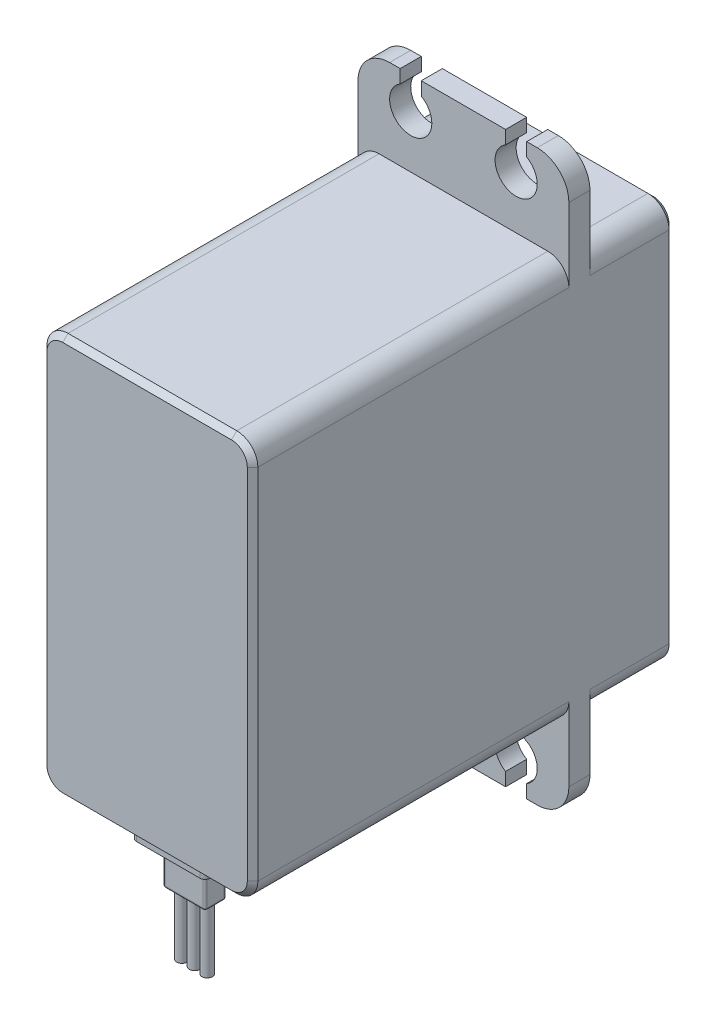
SolidWorks part; units mm, degrees
ref_plane "前视基准面" through (0, 0, 0) normal (0, 0, 1) x (1, 0, 0)
ref_plane "上视基准面" through (0, 0, 0) normal (0, 1, 0) x (1, 0, 0)
ref_plane "右视基准面" through (0, 0, 0) normal (1, 0, 0) x (0, 0, -1)
sketch "草图1" plane through (0, 0, 0) normal (0, 0, 1) x (1, 0, 0)
  line L1 (-10, -27) -> (10, -27)
  line L2 (-10, -27) -> (-10, 27)
  line L3 (-10, 27) -> (10, 27)
  line L4 (10, -27) -> (10, 27)
  line L5 (-10, -27) -> (10, 27) construction
  line L6 (-10, 27) -> (10, -27) construction
  point P0 (0, 0)
  dimension "D1" = 20
  dimension "D2" = 54
extrude "凸台-拉伸1" add sketch "草图1" along normal blind 40
sketch "草图2" plane through (0, 0, 40) normal (0, 0, 1) x (1, 0, 0)
  line L0 (10, -27) -> (10, 27) construction
  line L1 (-10, -19) -> (10, -19)
  line L2 (-10, -19) -> (-10, 19)
  line L3 (-10, 19) -> (10, 19)
  line L4 (10, -19) -> (10, 19)
  line L5 (-10, -19) -> (10, 19) construction
  line L6 (-10, 19) -> (10, -19) construction
  point P0 (0, 0)
  dimension "D1" = 38
extrude "切除-拉伸1" cut sketch "草图2" against normal blind 30 flip side to cut
sketch "草图3" plane through (0, 0, 0) normal (0, 0, -1) x (-1, 0, 0)
  line L0 (10, 27) -> (10, -27) construction
  line L1 (-10, -19) -> (10, -19)
  line L2 (-10, -19) -> (-10, 19)
  line L3 (-10, 19) -> (10, 19)
  line L4 (10, -19) -> (10, 19)
  line L5 (-10, -19) -> (10, 19) construction
  line L6 (-10, 19) -> (10, -19) construction
  point P0 (0, 0)
  dimension "D1" = 38
extrude "切除-拉伸2" cut sketch "草图3" against normal blind 8 flip side to cut
sketch "草图4" plane through (0, 0, 10) normal (0, 0, 1) x (1, 0, 0)
  line L0 (4, 25.7321) -> (4, 27)
  line L1 (10, 27) -> (-10, 27) construction
  line L2 (4, 27) -> (6, 27)
  line L3 (6, 27) -> (6, 25.7321)
  line L4 (5, 24) -> (5, 27) construction
  line L5 (10, 19) -> (10, 27) construction
  line L6 (-6, 25.7321) -> (-6, 27)
  line L7 (-4, 27) -> (-4, 25.7321)
  line L8 (-6, 27) -> (-4, 27)
  arc A0 (4, 25.7321) -> (6, 25.7321) centre (5, 24) ccw
  arc A1 (-6, 25.7321) -> (-4, 25.7321) centre (-5, 24) ccw
  dimension "D1" = 2
  dimension "D2" = 3
  dimension "D3" = 2
  dimension "D4" = 4
  dimension "D6" = 10
  dimension "D5" = 2
extrude "切除-拉伸3" cut sketch "草图4" against normal through all
mirror "镜向1" about plane through (0, 0, 0) normal (0, 1, 0) of "切除-拉伸3"
sketch "草图6" plane through (0, -19, 0) normal (0, -1, 0) x (1, 0, 0)
  line L0 (0, 0) -> (0, 40) construction
  line L1 (-10, 40) -> (10, 40) construction
  line L3 (3.5, 38) -> (-3.5, 38)
  line L4 (3.5, 38) -> (3.5, 33)
  line L5 (3.5, 33) -> (-3.5, 33)
  line L6 (-3.5, 38) -> (-3.5, 33)
  line L7 (3.5, 38) -> (-3.5, 33) construction
  line L8 (3.5, 33) -> (-3.5, 38) construction
  point P5 (0, 35.5)
  dimension "D1" = 7
  dimension "D2" = 5
  dimension "D3" = 2
extrude "凸台-拉伸2" add sketch "草图6" along normal blind 2
sketch "草图7" plane through (0, -21, 0) normal (0, -1, 0) x (1, 0, 0)
  line L0 (-3.5, 38) -> (3.5, 33) construction
  line L1 (-2, 34.5) -> (2, 34.5)
  line L2 (-2, 34.5) -> (-2, 36.5)
  line L3 (-2, 36.5) -> (2, 36.5)
  line L4 (2, 34.5) -> (2, 36.5)
  line L5 (-2, 34.5) -> (2, 36.5) construction
  line L6 (-2, 36.5) -> (2, 34.5) construction
  line L7 (-3.5, 38) -> (-3.5, 33) construction
  line L8 (3.5, 38) -> (-3.5, 38) construction
  line L9 (3.5, 38) -> (-3.5, 33) construction
  point P0 (0, 35.5)
  dimension "D1" = 4
  dimension "D2" = 2
extrude "凸台-拉伸3" add sketch "草图7" along normal blind 4
sketch "草图8" plane through (0, -25, 0) normal (0, -1, 0) x (1, 0, 0)
  line L0 (2, 34.5) -> (2, 36.5) construction
  line L1 (-2, 35.5) -> (2, 35.5) construction
  line L2 (-2, 36.5) -> (-2, 34.5) construction
  circle A0 centre (1.2, 35.5) radius 0.5
  circle A1 centre (0, 35.5) radius 0.5
  circle A2 centre (-1.2, 35.5) radius 0.5
  dimension "D1" = 1
  dimension "D2" = 0.8
  dimension "D3" = 1.2
  dimension "D4" = 1.2
extrude "凸台-拉伸4" add sketch "草图8" along normal blind 6
sketch "草图9" plane through (0, 0, 0) normal (0, 0, -1) x (-1, 0, 0)
  line L0 (-10, -19) -> (10, -19) construction
  circle A0 centre (0, -9) radius 6.5
  dimension "D1" = 10
  dimension "D2" = 13
extrude "凸台-拉伸5" add sketch "草图9" along normal blind 2
sketch "草图10" plane through (0, 0, -2) normal (0, 0, -1) x (-1, 0, 0)
  circle A0 centre (0, -9) radius 5
  dimension "D1" = 10
extrude "切除-拉伸4" cut sketch "草图10" against normal blind 0.8
sketch "草图11" plane through (0, 0, -1.2) normal (0, 0, -1) x (-1, 0, 0)
  circle A0 centre (0, -9) radius 2.5
  dimension "D1" = 5
extrude "切除-拉伸5" cut sketch "草图11" against normal blind 4
sketch "草图12" plane through (0, 0, 2.8) normal (0, 0, -1) x (-1, 0, 0)
  circle A0 centre (0, -9) radius 2.5 construction
  circle A1 centre (0, -9) radius 2.5
extrude "凸台-拉伸6" add sketch "草图12" along normal blind 10 separate body
sketch "草图13" plane through (0, 0, -7.2) normal (0, 0, -1) x (-1, 0, 0)
  line L0 (0, -9) -> (0, -6.5) construction
  line L1 (-0.2796, -6.5157) -> (0, -7)
  line L2 (0, -7) -> (0.2796, -6.5157)
  line L3 (0.5018, -6.5509) -> (0.618, -7.0979)
  line L4 (0.618, -7.0979) -> (1.0336, -6.7237)
  line L5 (1.234, -6.8258) -> (1.1756, -7.382)
  line L6 (1.1756, -7.382) -> (1.6865, -7.1545)
  line L7 (1.8455, -7.3135) -> (1.618, -7.8244)
  line L8 (1.618, -7.8244) -> (2.1742, -7.766)
  line L9 (2.2763, -7.9664) -> (1.9021, -8.382)
  line L10 (1.9021, -8.382) -> (2.4491, -8.4982)
  line L11 (2.4843, -8.7204) -> (2, -9)
  line L12 (2, -9) -> (2.4843, -9.2796)
  line L13 (2.4491, -9.5018) -> (1.9021, -9.618)
  line L14 (1.9021, -9.618) -> (2.2763, -10.0336)
  line L15 (2.1742, -10.234) -> (1.618, -10.1756)
  line L16 (1.618, -10.1756) -> (1.8455, -10.6865)
  line L17 (1.6865, -10.8455) -> (1.1756, -10.618)
  line L18 (1.1756, -10.618) -> (1.234, -11.1742)
  line L19 (1.0336, -11.2763) -> (0.618, -10.9021)
  line L20 (0.618, -10.9021) -> (0.5018, -11.4491)
  line L21 (0.2796, -11.4843) -> (0, -11)
  line L22 (0, -11) -> (-0.2796, -11.4843)
  line L23 (-0.5018, -11.4491) -> (-0.618, -10.9021)
  line L24 (-0.618, -10.9021) -> (-1.0336, -11.2763)
  line L25 (-1.234, -11.1742) -> (-1.1756, -10.618)
  line L26 (-1.1756, -10.618) -> (-1.6865, -10.8455)
  line L27 (-1.8455, -10.6865) -> (-1.618, -10.1756)
  line L28 (-1.618, -10.1756) -> (-2.1742, -10.234)
  line L29 (-2.2763, -10.0336) -> (-1.9021, -9.618)
  line L30 (-1.9021, -9.618) -> (-2.4491, -9.5018)
  line L31 (-2.4843, -9.2796) -> (-2, -9)
  line L32 (-2, -9) -> (-2.4843, -8.7204)
  line L33 (-2.4491, -8.4982) -> (-1.9021, -8.382)
  line L34 (-1.9021, -8.382) -> (-2.2763, -7.9664)
  line L35 (-2.1742, -7.766) -> (-1.618, -7.8244)
  line L36 (-1.618, -7.8244) -> (-1.8455, -7.3135)
  line L37 (-1.6865, -7.1545) -> (-1.1756, -7.382)
  line L38 (-1.1756, -7.382) -> (-1.234, -6.8258)
  line L39 (-1.0336, -6.7237) -> (-0.618, -7.0979)
  line L40 (-0.618, -7.0979) -> (-0.5018, -6.5509)
  circle A0 centre (0, -9) radius 2.5 construction
  circle A1 centre (0, -9) radius 2.5 construction
  arc A2 (0.2796, -6.5157) -> (-0.2796, -6.5157) centre (0, -9) ccw
  arc A3 (1.0336, -6.7237) -> (0.5018, -6.5509) centre (0, -9) ccw
  arc A4 (1.6865, -7.1545) -> (1.234, -6.8258) centre (0, -9) ccw
  arc A5 (2.1742, -7.766) -> (1.8455, -7.3135) centre (0, -9) ccw
  arc A6 (2.4491, -8.4982) -> (2.2763, -7.9664) centre (0, -9) ccw
  arc A7 (2.4843, -9.2796) -> (2.4843, -8.7204) centre (0, -9) ccw
  arc A8 (2.2763, -10.0336) -> (2.4491, -9.5018) centre (0, -9) ccw
  arc A9 (1.8455, -10.6865) -> (2.1742, -10.234) centre (0, -9) ccw
  arc A10 (1.234, -11.1742) -> (1.6865, -10.8455) centre (0, -9) ccw
  arc A11 (0.5018, -11.4491) -> (1.0336, -11.2763) centre (0, -9) ccw
  arc A12 (-0.2796, -11.4843) -> (0.2796, -11.4843) centre (0, -9) ccw
  arc A13 (-1.0336, -11.2763) -> (-0.5018, -11.4491) centre (0, -9) ccw
  arc A14 (-1.6865, -10.8455) -> (-1.234, -11.1742) centre (0, -9) ccw
  arc A15 (-2.1742, -10.234) -> (-1.8455, -10.6865) centre (0, -9) ccw
  arc A16 (-2.4491, -9.5018) -> (-2.2763, -10.0336) centre (0, -9) ccw
  arc A17 (-2.4843, -8.7204) -> (-2.4843, -9.2796) centre (0, -9) ccw
  arc A18 (-2.2763, -7.9664) -> (-2.4491, -8.4982) centre (0, -9) ccw
  arc A19 (-1.8455, -7.3135) -> (-2.1742, -7.766) centre (0, -9) ccw
  arc A20 (-1.234, -6.8258) -> (-1.6865, -7.1545) centre (0, -9) ccw
  arc A21 (-0.5018, -6.5509) -> (-1.0336, -6.7237) centre (0, -9) ccw
  point P70 (0, -9)
  dimension "D1" = 2
  dimension "D2" = 60
  dimension "D3" = 20
extrude "切除-拉伸6" cut sketch "草图13" against normal through all
sketch "草图14" plane through (0, 0, 0) normal (1, 0, 0) x (0, 0, -1)
  line L0 (7.2, -7) -> (7.2, -6)
  line L1 (7.2, -7.382) -> (7.2, -6.8258) construction
  line L2 (7.2, -6) -> (6.6226, -6)
  line L3 (6.6226, -6) -> (7.2, -7)
  dimension "D1" = 30
  dimension "D2" = 1
revolve "切除-旋转1" cut sketch "草图14" angle 360 about axis through (0, -9, -7.2) along (0, 0, 1)
ref_plane "基准面1" through (0, 0, -2.2) normal (0, 0, 1) x (1, 0, 0)
mirror "镜向2" about plane through (0, 0, -2.2) normal (0, 0, 1) of "切除-旋转1"
fillet "圆角1" radius 2 8 edges at (-10, -19, 4) (-10, -19, 25) (10, -19, 4) (10, -19, 25) (-10, 19, 4) (-10, 19, 25) (10, 19, 4) (10, 19, 25)
chamfer "倒角1" distance 0.5 angle 45 17 edges at (0, 19, 0) (-10, 0, 0) (0, -19, 0) (10, 0, 0) (-10, 0, 40) (0, -19, 40) (10, 0, 40) (0, 19, 40) (-9.4142, -18.4142, 0) (-9.4142, 18.4142, 0) (9.4142, -18.4142, 0) (9.4142, 18.4142, 0) (9.4142, -18.4142, 40) (-9.4142, -18.4142, 40) (9.4142, 18.4142, 40) (-9.4142, 18.4142, 40) (-6.5, -9, -2)
fillet "圆角2" radius 3 4 edges at (10, -27, 9) (-10, -27, 9) (-10, 27, 9) (10, 27, 9)
fillet "圆角3" radius 0.5 4 edges at (-3.5, -20, 38) (3.5, -20, 33) (-3.5, -20, 33) (3.5, -20, 38)
fillet "圆角4" radius 0.2 8 edges at (2, -23, 34.5) (-2, -23, 34.5) (-2, -23, 36.5) (2, -23, 36.5) (0, -25, 34.5) (-2, -25, 35.5) (0, -25, 36.5) (2, -25, 35.5)
hole_wizard "M2 螺纹孔2" positions "3D草图3" profile "草图17" tap size "M2" standard "GB"
sketch3d "3D草图3"
  arc A0 (0.618, -7.0979, -7.2) -> (1.1756, -7.382, -7.2) centre (0, -9, -7.2) ccw construction
  point P0 (0, -9, -7.2)
  point P7 (0, -9, -9.2)
sketch "草图17" plane through (0, -9, -7.2) normal (1, 0, 0) x (0, 1, 0)
  line L0 (0, 0) -> (0, 10.4807)
  line L1 (0, 10.4807) -> (0.8, 10)
  line L2 (0.8, 10) -> (0.8, 0)
  line L5 (0.8, 0) -> (0, 0)
  line L10 (0, 10.4807) -> (-0.8, 10) construction
  line L11 (0, -6.35) -> (0, 107.95) construction
  dimension "螺纹孔钻头直径" = 1.6
  dimension "螺纹孔钻头深度" = 10
  dimension "导头角度" = 118
cosmetic thread "孔螺蚊线10"
move or copy body "实体-移动/复制1" [suppressed] bodies to move or copy 123 124
move or copy body "实体-移动/复制2" [suppressed] bodies to move or copy 125 126 parameters "D1"=0, "D2"=0, "D3"=0
move or copy body "实体-移动/复制3" [suppressed] bodies to move or copy 127 128 parameters "D1"=0, "D2"=0, "D3"=0
